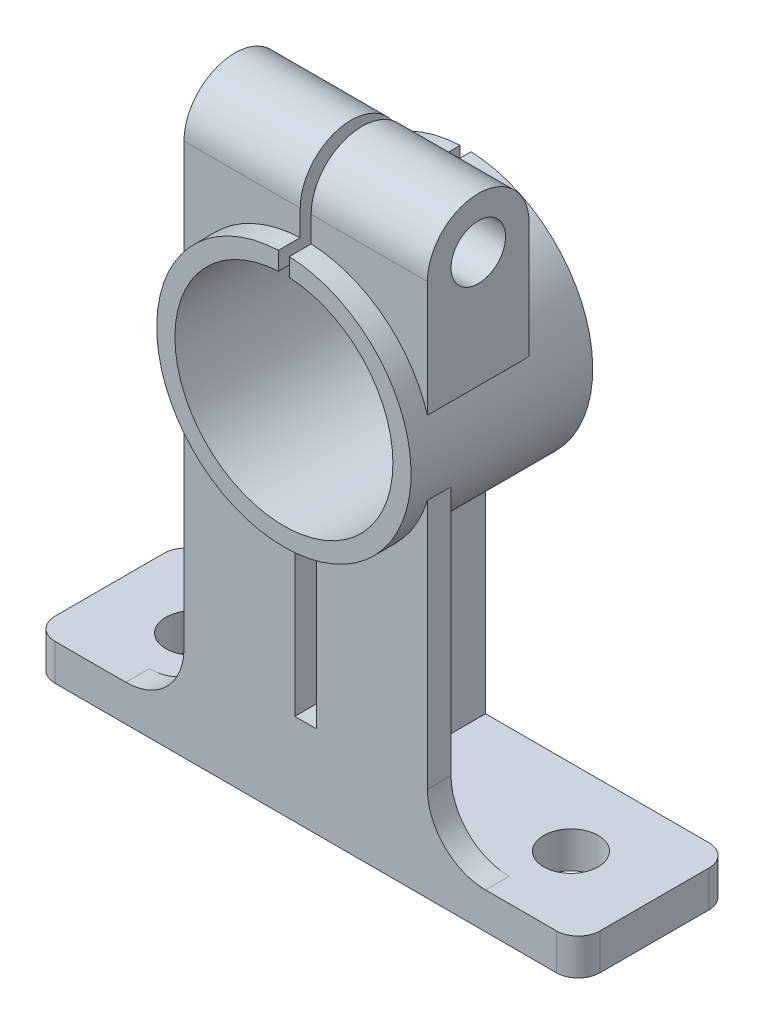
SolidWorks part; units mm, degrees
ref_plane "Front Plane" through (0, 0, 0) normal (0, 0, 1) x (1, 0, 0)
ref_plane "Top Plane" through (0, 0, 0) normal (0, 1, 0) x (1, 0, 0)
ref_plane "Right Plane" through (0, 0, 0) normal (1, 0, 0) x (0, 0, -1)
sketch "Sketch1" plane through (0, 0, 0) normal (0, 0, 1) x (1, 0, 0)
  circle A0 centre (0, 0) radius 30
  circle A1 centre (0, 0) radius 35
  dimension "D1" = 70
  dimension "D2" = 60
extrude "Boss-Extrude1" add sketch "Sketch1" along normal blind 50
ref_plane "Plane2" through (0, 0, 2) normal (0, 0, 1) x (1, 0, 0)
sketch "Sketch4" plane through (0, 0, 2) normal (0, 0, 1) x (1, 0, 0)
  line L0 (0, 0) -> (0, -105) construction
  line L1 (-75, -95) -> (75, -95)
  line L2 (-75, -95) -> (-75, -105)
  line L3 (-75, -105) -> (75, -105)
  line L4 (75, -95) -> (75, -105)
  dimension "D1" = 105
  dimension "D2" = 10
  dimension "D3" = 150
extrude "Boss-Extrude3" add sketch "Sketch4" along normal blind 42 separate body
ref_plane "Plane3" through (0, 0, 44) normal (0, 0, 1) x (1, 0, 0)
sketch "Sketch5" plane through (0, 0, 44) normal (0, 0, 1) x (1, 0, 0)
  line L0 (-33.5, -10.1366) -> (-33.5, -95)
  line L1 (33.5, -10.1366) -> (33.5, -95)
  line L2 (0, 0) -> (0, -95) construction
  line L3 (75, -95) -> (-75, -95) construction
  line L4 (-33.5, -95) -> (33.5, -95)
  circle A0 centre (0, 0) radius 35 construction
  arc A1 (-33.5, -10.1366) -> (33.5, -10.1366) centre (0, 0) ccw
  dimension "D3" = 35
  dimension "D1" = 33.5
  dimension "D2" = 67
extrude "Boss-Extrude5" add sketch "Sketch5" against normal blind 6.5 contours L0 L4 L1 A1
fillet "Fillet1" radius 16 2 edges at (33.5, -95, 40.75) (-33.5, -95, 40.75)
sketch "Sketch8" plane through (0, 0, 0) normal (1, 0, 0) x (0, 0, -1)
  line L0 (-37.5, -35) -> (-37.5, -10.1366) construction
  line L1 (-2, -95) -> (-37.5, -95)
  line L2 (-2, -95) -> (-2, -30.7545)
  line L3 (-2, -30.7545) -> (-37.5, -30.7545)
  line L4 (-37.5, -95) -> (-37.5, -30.7545)
  dimension "D1" = 74.2455
extrude "Boss-Extrude6" add sketch "Sketch8" along normal mid plane 15
sketch "Sketch9" plane through (0, 0, 44) normal (0, 0, 1) x (1, 0, 0)
  line L0 (0, 0) -> (0, -105) construction
  line L1 (-3, -34.8712) -> (3, -34.8712)
  line L2 (-3, -34.8712) -> (-3, -79.8712)
  line L3 (-3, -79.8712) -> (3, -79.8712)
  line L4 (3, -34.8712) -> (3, -79.8712)
  line L5 (-75, -105) -> (75, -105) construction
  arc A0 (-33.5, -10.1366) -> (33.5, -10.1366) centre (0, 0) ccw construction
  dimension "D1" = 3
  dimension "D2" = 6
  dimension "D3" = 45
extrude "Cut-Extrude1" cut sketch "Sketch9" against normal through all
ref_plane "Plane4" through (33.5, 0, 0) normal (1, 0, 0) x (0, 0, -1)
sketch "Sketch10" plane through (33.5, 0, 0) normal (1, 0, 0) x (0, 0, -1)
  line L0 (-44, 42) -> (-44, 7)
  line L2 (-16, 42) -> (-16, 7)
  line L3 (-16, 7) -> (-44, 7)
  circle A0 centre (-30, 42) radius 7.5
  arc A1 (-16, 42) -> (-44, 42) centre (-30, 42) ccw
  dimension "D2" = 15
  dimension "D3" = 28
  dimension "D1" = 137
  dimension "D4" = 35
extrude "Boss-Extrude8" add sketch "Sketch10" against normal blind 67
sketch "Sketch12" plane through (0, 0, 44) normal (0, 0, 1) x (1, 0, 0)
  circle A0 centre (0, 0) radius 30
  dimension "D1" = 60
extrude "Cut-Extrude3" cut sketch "Sketch12" against normal blind 67
sketch "Sketch13" plane through (0, 0, 50) normal (0, 0, 1) x (1, 0, 0)
  line L0 (0, 0) -> (0, 60.0192) construction
  line L1 (1.5, 8.5916) -> (-1.5, 8.5916)
  line L2 (1.5, 8.5916) -> (1.5, 60.0192)
  line L3 (1.5, 60.0192) -> (-1.5, 60.0192)
  line L4 (-1.5, 8.5916) -> (-1.5, 60.0192)
  dimension "D1" = 1.5
  dimension "D2" = 51.4276
  dimension "D3" = 8.5916
extrude "Cut-Extrude4" cut sketch "Sketch13" against normal blind 67
sketch "Sketch15" plane through (0, 0, 0) normal (0, 1, 0) x (1, 0, 0)
  line L1 (-75, -23) -> (75, -23) construction
  line L2 (-75, -44) -> (-75, -2) construction
  line L3 (75, -44) -> (75, -2) construction
  circle A0 centre (-52, -23) radius 7.5
  circle A1 centre (52, -23) radius 7.5
  dimension "D1" = 15
  dimension "D2" = 15
  dimension "D3" = 23
  dimension "D4" = 23
extrude "Cut-Extrude5" cut sketch "Sketch15" against normal blind 113
fillet "Fillet2" radius 6 4 edges at (75, -100, 2) (75, -100, 44) (-75, -100, 2) (-75, -100, 44)
